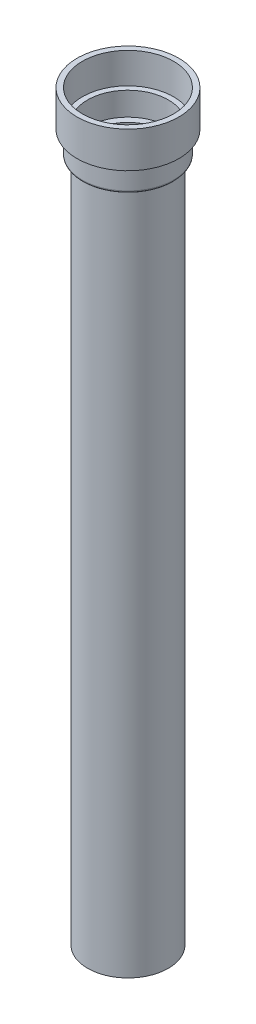
SolidWorks part; units mm, degrees
ref_plane "Front Plane" through (0, 0, 0) normal (0, 0, 1) x (1, 0, 0)
ref_plane "Top Plane" through (0, 0, 0) normal (0, 1, 0) x (1, 0, 0)
ref_plane "Right Plane" through (0, 0, 0) normal (1, 0, 0) x (0, 0, -1)
sketch "Sketch1" plane through (0, 0, 0) normal (1, 0, 0) x (0, 0, -1)
  line L0 (0, 0) -> (0, -350) construction
  line L1 (-21.5, 0) -> (-24, 0)
  line L2 (-24, 0) -> (-24, -17)
  line L3 (-24, -17) -> (-21.5, -17)
  line L4 (-21.5, -17) -> (-21.5, -28)
  line L5 (-21.5, -28) -> (-19, -28)
  line L6 (-19, -28) -> (-19, -350)
  line L7 (-19, -350) -> (0, -350)
  line L8 (0, -350) -> (0, -347.5)
  line L9 (-21.5, 0) -> (-21.5, -14.5)
  line L10 (-21.5, -14.5) -> (-19, -14.5)
  line L11 (-19, -14.5) -> (-19, -25.5)
  line L12 (-19, -25.5) -> (-16, -25.5)
  line L13 (-16, -25.5) -> (-16, -345.4358)
  line L14 (0, -347.5) -> (-16, -347.5)
  line L15 (-16, -345.4358) -> (-16, -347.5)
  dimension "D1" = 350
  dimension "D2" = 24
  dimension "D3" = 17
  dimension "D4" = 2.5
  dimension "D5" = 11
  dimension "D6" = 2.5
  dimension "D7" = 14.5
  dimension "D8" = 11
  dimension "D9" = 3
  dimension "D10" = 2.5
  dimension "D11" = 16
revolve "Revolve1" add sketch "Sketch1" angle 360 about L0
fillet "Fillet2" radius 1 1 edges at (0, -28, 21.5)
